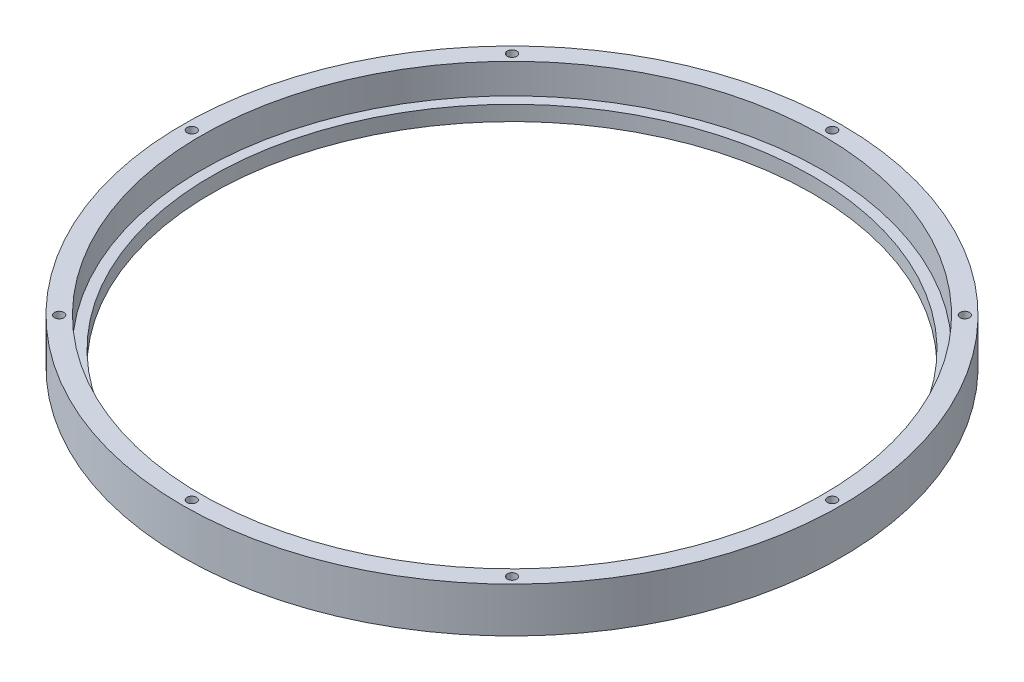
SolidWorks part; units mm, degrees
material "6061-T6 (SS)"
ref_plane "前视基准面" through (0, 0, 0) normal (0, 0, 1) x (1, 0, 0)
ref_plane "上视基准面" through (0, 0, 0) normal (0, 1, 0) x (1, 0, 0)
ref_plane "右视基准面" through (0, 0, 0) normal (1, 0, 0) x (0, 0, -1)
sketch "草图1" plane through (0, 0, 0) normal (0, 0, 1) x (1, 0, 0)
  line L0 (0, 172.8551) -> (0, -190.8081) construction
  line L1 (-240.7542, 0) -> (186.8953, 0) construction
  line L2 (80.25, 0) -> (88, 0)
  line L3 (88, 0) -> (88, 12)
  line L4 (88, 12) -> (83, 12)
  line L5 (83, 12) -> (83, 4)
  line L6 (83, 4) -> (80.25, 4)
  line L7 (80.25, 4) -> (80.25, 0)
  dimension "D1" = 160.5
  dimension "D2" = 166
  dimension "D3" = 4
  dimension "D4" = 8
  dimension "D5" = 5
  dimension "D6" = 176
revolve "旋转1" add sketch "草图1" angle 360 about L0
sketch "草图2" plane through (0, 12, 0) normal (0, 1, 0) x (1, 0, 0)
  circle A0 centre (0, 0) radius 85.5 construction
  point P3 (60.4576, 60.4576)
  point P5 (0, 85.5)
  point P7 (85.5, 0)
  point P8 (60.4576, -60.4576)
  point P9 (0, -85.5)
  point P10 (-60.4576, -60.4576)
  point P11 (-85.5, 0)
  point P12 (-60.4576, 60.4576)
  point P13 (0, 0)
  dimension "D1" = 171
  dimension "D2" = 8
hole_wizard "M3 螺纹孔1" positions "草图5" profile "草图4" tap size "M3" standard "GB" end condition through all
sketch "草图5" plane through (0, 12, 0) normal (0, 1, 0) x (1, 0, 0)
  point P0 (-60.4576, 60.4576)
  point P3 (-85.5, 0)
  point P6 (0, 85.5)
  point P9 (60.4576, 60.4576)
  point P12 (85.5, 0)
  point P15 (60.4576, -60.4576)
  point P18 (0, -85.5)
  point P21 (-60.4576, -60.4576)
sketch "草图4" plane through (-60.4576, 12, -60.4576) normal (1, 0, 0) x (0, 0, 1)
  line L0 (0, 0) -> (0, 12)
  line L1 (0, 12) -> (1.25, 12)
  line L2 (1.25, 12) -> (1.25, 0)
  line L5 (1.25, 0) -> (0, 0)
  line L11 (0, -6.35) -> (0, 107.95) construction
  dimension "通孔螺纹孔钻头直径" = 2.5
  dimension "通孔螺纹孔钻头深度" = 12
cosmetic thread "孔螺蚊线1" parameters "D2"=3
cosmetic thread "孔螺蚊线2" parameters "D2"=3
cosmetic thread "孔螺蚊线3" parameters "D2"=3
cosmetic thread "孔螺蚊线4" parameters "D2"=3
cosmetic thread "孔螺蚊线5" parameters "D2"=3
cosmetic thread "孔螺蚊线6" parameters "D2"=3
cosmetic thread "孔螺蚊线7" parameters "D2"=3
cosmetic thread "孔螺蚊线8" parameters "D2"=3
move or copy body "实体-移动/复制1" bodies to move or copy 107
